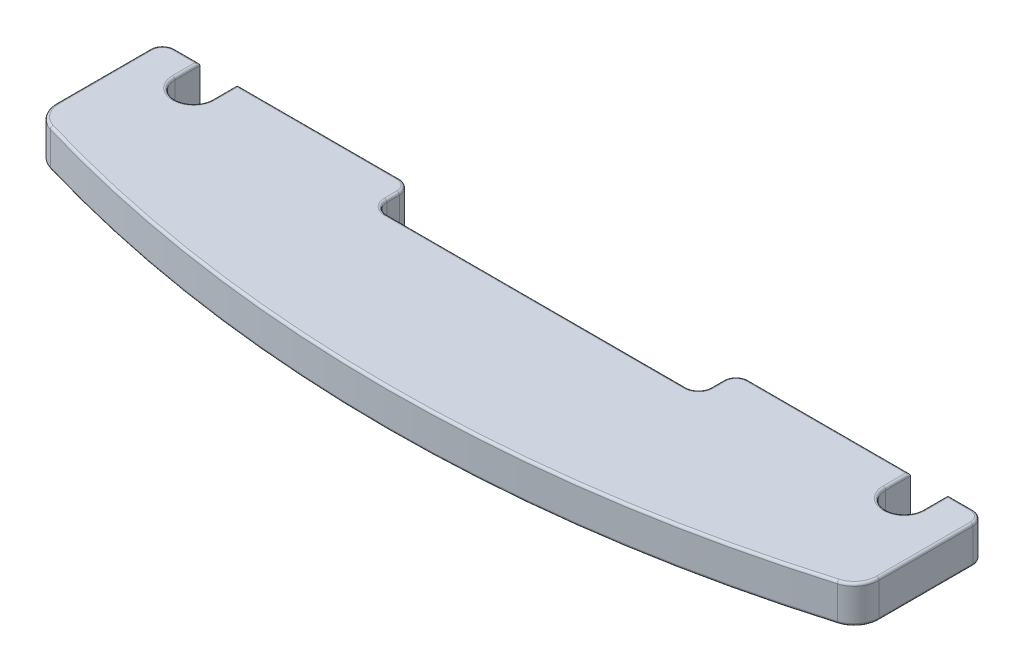
SolidWorks part; units mm, degrees
ref_plane "Front Plane" through (0, 0, 0) normal (0, 0, 1) x (1, 0, 0)
ref_plane "Top Plane" through (0, 0, 0) normal (0, 1, 0) x (1, 0, 0)
ref_plane "Right Plane" through (0, 0, 0) normal (1, 0, 0) x (0, 0, -1)
sketch "Sketch1" plane through (0, 0, 0) normal (0, 1, 0) x (1, 0, 0)
  line L0 (0, 0) -> (0, 12) construction
  line L1 (-33, 14) -> (-33, 6.484)
  line L2 (-32, 15) -> (-30, 15)
  line L3 (-13, 14) -> (-13, 13)
  line L4 (-12, 12) -> (12, 12)
  line L5 (-30, 13) -> (-30, 15)
  line L6 (-27, 13) -> (-27, 15)
  line L7 (-27, 15) -> (-14, 15)
  line L8 (27, 15) -> (14, 15)
  line L9 (27, 13) -> (27, 15)
  line L10 (30, 13) -> (30, 15)
  line L11 (13, 14) -> (13, 13)
  line L12 (32, 15) -> (30, 15)
  line L13 (33, 14) -> (33, 6.484)
  arc A0 (-31.5667, 4.566) -> (31.5667, 4.566) centre (0, 111.4) ccw
  arc A1 (-30, 13) -> (-27, 13) centre (-28.5, 13) ccw
  arc A2 (-13, 13) -> (-12, 12) centre (-12, 13) ccw
  arc A3 (-13, 14) -> (-14, 15) centre (-14, 14) ccw
  arc A4 (-33, 14) -> (-32, 15) centre (-32, 14) cw
  arc A5 (-31.5667, 4.566) -> (-33, 6.484) centre (-31, 6.484) cw
  arc A6 (31.5667, 4.566) -> (33, 6.484) centre (31, 6.484) ccw
  arc A7 (33, 14) -> (32, 15) centre (32, 14) ccw
  arc A8 (13, 14) -> (14, 15) centre (14, 14) cw
  arc A9 (13, 13) -> (12, 12) centre (12, 13) cw
  arc A10 (30, 13) -> (27, 13) centre (28.5, 13) cw
  point P16 (-13, 12)
  point P19 (-13, 15)
  point P22 (-33, 15)
  point P25 (-33, 5)
  point P27 (0, 12)
  point P43 (33, 5)
  point P44 (33, 15)
  point P45 (13, 15)
  point P46 (13, 12)
  dimension "D1" = 10
  dimension "D6" = 3
  dimension "D9" = 1
  dimension "D10" = 2
  dimension "D2" = 33
  dimension "D3" = 15
  dimension "D4" = 3
  dimension "D5" = 20
  dimension "D7" = 30
  dimension "D8" = 2
extrude "Boss-Extrude1" add sketch "Sketch1" along normal blind 3
fillet "Fillet1" radius 0.2 48 edges at (-13, 0, -13.5) (-13.2929, 0, -14.7071) (-20.5, 0, -15) (-27, 0, -14) (-28.5, 0, -11.5) (-30, 0, -14) (-31, 0, -15) (-32.7071, 0, -14.7071) (-33, 0, -10.242) (-32.6021, 0, -5.2868) (0, 0, 0) (32.6021, 0, -5.2868) (33, 0, -10.242) (32.7071, 0, -14.7071) (31, 0, -15) (30, 0, -14) (28.5, 0, -11.5) (27, 0, -14) (20.5, 0, -15) (13.2929, 0, -14.7071) (13, 0, -13.5) (12.7071, 0, -12.2929) (0, 0, -12) (-12.7071, 0, -12.2929) (0, 3, -12) (12.7071, 3, -12.2929) (13, 3, -13.5) (13.2929, 3, -14.7071) (20.5, 3, -15) (27, 3, -14) (28.5, 3, -11.5) (30, 3, -14) (31, 3, -15) (32.7071, 3, -14.7071) (33, 3, -10.242) (32.6021, 3, -5.2868) (0, 3, 0) (-32.6021, 3, -5.2868) (-33, 3, -10.242) (-32.7071, 3, -14.7071) (-31, 3, -15) (-30, 3, -14) (-28.5, 3, -11.5) (-27, 3, -14) (-20.5, 3, -15) (-13.2929, 3, -14.7071) (-13, 3, -13.5) (-12.7071, 3, -12.2929)
ref_plane "Plane1" through (0, 0, -13) normal (0, 0, 1) x (0, -1, 0)
